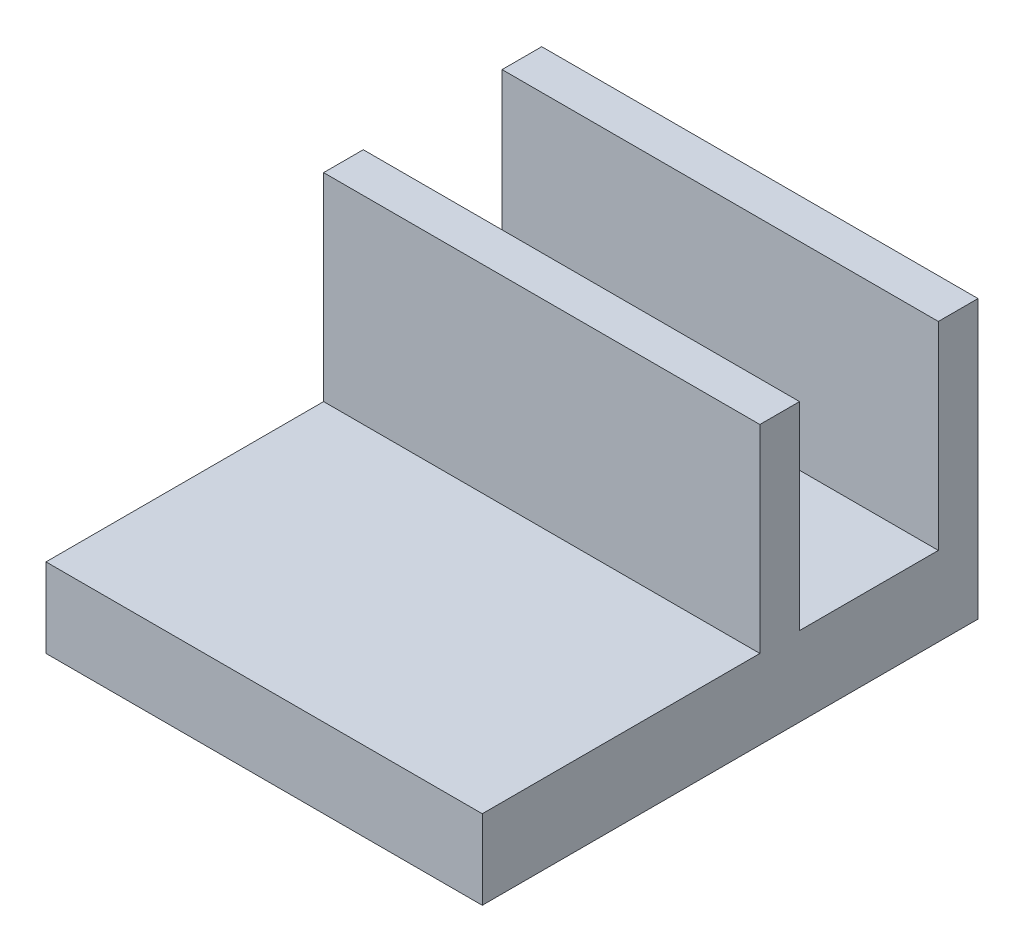
SolidWorks part; units mm, degrees
ref_plane "Спереди" through (0, 0, 0) normal (0, 0, 1) x (1, 0, 0)
ref_plane "Сверху" through (0, 0, 0) normal (0, 1, 0) x (1, 0, 0)
ref_plane "Справа" through (0, 0, 0) normal (1, 0, 0) x (0, 0, -1)
sketch "Эскиз2" plane through (0, 0, 0) normal (0, 1, 0) x (1, 0, 0)
  line L1 (-45.832, -5.4416) -> (-23.832, -5.4416)
  line L2 (-45.832, -5.4416) -> (-45.832, -30.4416)
  line L3 (-45.832, -30.4416) -> (-23.832, -30.4416)
  line L4 (-23.832, -5.4416) -> (-23.832, -30.4416)
extrude "Бобышка-Вытянуть1" add sketch "Эскиз2" along normal blind 4
sketch "Эскиз3" plane through (0, 4, 0) normal (0, 1, 0) x (1, 0, 0)
  line L0 (-23.832, -30.4416) -> (-23.832, -5.4416) construction
  line L1 (-45.832, -5.4416) -> (-23.832, -5.4416)
  line L2 (-45.832, -5.4416) -> (-45.832, -7.4416)
  line L3 (-45.832, -7.4416) -> (-23.832, -7.4416)
  line L4 (-23.832, -5.4416) -> (-23.832, -7.4416)
  line L5 (-45.832, -14.4416) -> (-23.832, -14.4416)
  line L6 (-45.832, -5.4416) -> (-45.832, -30.4416) construction
  line L7 (-45.832, -16.4416) -> (-23.832, -16.4416)
  line M4 (-45.832, -5.4416) -> (-45.832, -30.4416)
  line M6 (-23.832, -30.4416) -> (-23.832, -5.4416)
  line M7 (-23.832, -5.4416) -> (-45.832, -5.4416)
  dimension "D1" = 7
  dimension "D2" = 2
  dimension "D3" = 2
extrude "Бобышка-Вытянуть2" add sketch "Эскиз3" along normal blind 10 contours L3 M4 M6 M7 | L7 L5 M4 M6
